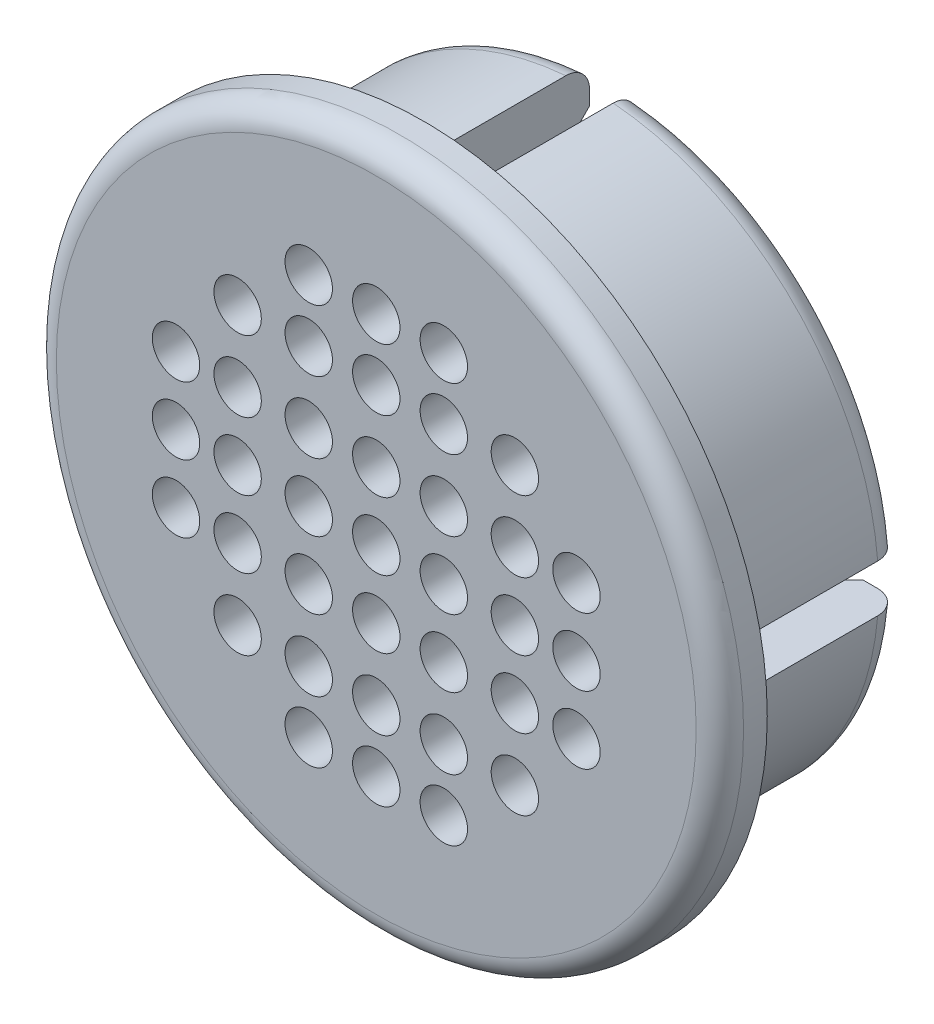
SolidWorks part; units mm, degrees
ref_plane "Front Plane" through (0, 0, 0) normal (0, 0, 1) x (1, 0, 0)
ref_plane "Top Plane" through (0, 0, 0) normal (0, 1, 0) x (1, 0, 0)
ref_plane "Right Plane" through (0, 0, 0) normal (1, 0, 0) x (0, 0, -1)
sketch "Sketch2" plane through (0, 0, 0) normal (1, 0, 0) x (0, 0, -1)
  line L0 (0, 0) -> (10, 0) construction
  line L1 (0, 0) -> (0, 7.25)
  line L2 (0, 7.25) -> (1, 7.25)
  line L3 (1, 7.25) -> (1, 6.1)
  line L4 (1, 6.1) -> (5, 6.1)
  line L5 (5, 6.1) -> (5, 5.1)
  line L6 (5, 5.1) -> (1, 5.1)
  line L7 (1, 5.1) -> (1, 0)
  line L8 (1, 0) -> (0, 0)
  dimension "D1" = 10
  dimension "D2" = 7.25
  dimension "D3" = 5.1
  dimension "D4" = 6.1
  dimension "D5" = 5
  dimension "D6" = 1
  dimension "D7" = 1
revolve "Revolve1" add sketch "Sketch2" angle 360 about L0
sketch "Sketch3" plane through (0, 0, 0) normal (0, 0, 1) x (1, 0, 0)
  line L0 (-2.925, 2.925) -> (2.925, 2.925)
  line L1 (-1.425, 1.425) -> (1.425, 1.425)
  line L2 (-1.425, 1.425) -> (-1.425, -1.425)
  line L3 (-1.425, -1.425) -> (1.425, -1.425)
  line L4 (1.425, 1.425) -> (1.425, -1.425)
  line L5 (-1.425, 1.425) -> (1.425, -1.425) construction
  line L6 (-1.425, -1.425) -> (1.425, 1.425) construction
  line L7 (2.925, 2.925) -> (2.925, -2.925)
  line L8 (-2.925, -2.925) -> (2.925, -2.925)
  line L9 (-2.925, 2.925) -> (-2.925, -2.925)
  line L10 (-2.925, 2.925) -> (0, 2.925) construction
  line L11 (0, 2.925) -> (2.925, 2.925) construction
  line L12 (-4.225, 4.225) -> (4.225, 4.225)
  line L13 (4.225, 4.225) -> (4.225, -4.225)
  line L14 (-4.225, -4.225) -> (4.225, -4.225)
  line L15 (-4.225, 4.225) -> (-4.225, -4.225)
  circle A0 centre (-1.425, 1.425) radius 0.5
  circle A1 centre (1.425, 1.425) radius 0.5
  circle A2 centre (0, 1.425) radius 0.5
  circle A3 centre (1.425, 0) radius 0.5
  circle A4 centre (1.425, -1.425) radius 0.5
  circle A5 centre (0, -1.425) radius 0.5
  circle A6 centre (-1.425, -1.425) radius 0.5
  circle A7 centre (-1.425, 0) radius 0.5
  circle A9 centre (-2.925, 2.925) radius 0.5
  circle A10 centre (0, 2.925) radius 0.5
  circle A11 centre (2.925, 2.925) radius 0.5
  circle A12 centre (2.925, 0) radius 0.5
  circle A13 centre (2.925, -2.925) radius 0.5
  circle A14 centre (0, -2.925) radius 0.5
  circle A15 centre (-2.925, -2.925) radius 0.5
  circle A16 centre (-2.925, 0) radius 0.5
  circle A17 centre (0, 0) radius 5.1
  circle A18 centre (-1.425, 2.925) radius 0.5
  circle A19 centre (1.425, 2.925) radius 0.5
  circle A20 centre (2.925, 1.425) radius 0.5
  circle A21 centre (2.925, -1.425) radius 0.5
  circle A22 centre (1.425, -2.925) radius 0.5
  circle A23 centre (-1.425, -2.925) radius 0.5
  circle A24 centre (-2.925, -1.425) radius 0.5
  circle A25 centre (-2.925, 1.425) radius 0.5
  circle A26 centre (-1.425, 4.225) radius 0.5
  circle A27 centre (0, 4.225) radius 0.5
  circle A28 centre (1.425, 4.225) radius 0.5
  circle A29 centre (4.225, 1.425) radius 0.5
  circle A30 centre (4.225, 0) radius 0.5
  circle A31 centre (4.225, -1.425) radius 0.5
  circle A32 centre (1.425, -4.225) radius 0.5
  circle A33 centre (0, -4.225) radius 0.5
  circle A34 centre (-1.425, -4.225) radius 0.5
  circle A35 centre (-4.225, -1.425) radius 0.5
  circle A36 centre (-4.225, 0) radius 0.5
  circle A37 centre (-4.225, 1.425) radius 0.5
  circle A38 centre (0, 0) radius 0.5
  point P0 (0, 0)
  dimension "D3" = 1
  dimension "D4" = 1
  dimension "D5" = 1
  dimension "D6" = 1
  dimension "D7" = 1
  dimension "D8" = 1
  dimension "D9" = 1
  dimension "D10" = 1
  dimension "D12" = 10.2
  dimension "D14" = 1
  dimension "D1" = 2.85
  dimension "D2" = 2.85
  dimension "D11" = 1.5
  dimension "D13" = 1.3
extrude "Cut-Extrude1" cut sketch "Sketch3" against normal blind 10 contours A26 | A27 | A28 | A19 | A11 | A10 | A18 | A9 | A37 | A25 | A0 | A2 | A1 | A20 | A29 | A30 | A12 | A3 | A7 | A16 | A36 | A35 | A24 | A6 | A5 | A4 | A21 | A31 | A13 | A22 | A14 | A23 | A15 | A34 | A33 | A32 | A38
fillet "Fillet1" radius 0.5 2 edges at (6.1, 0, -5) (7.25, 0, 0)
chamfer "Chamfer1" distance 0.2 angle 45 1 edges at (5.1, 0, -5)
sketch "Sketch4" plane through (0, 0, -5) normal (0, 0, -1) x (-1, 0, 0)
  line L1 (0.5, -6.25) -> (-0.5, -6.25)
  line L2 (0.5, -6.25) -> (0.5, 6.25)
  line L3 (0.5, 6.25) -> (-0.5, 6.25)
  line L4 (-0.5, -6.25) -> (-0.5, 6.25)
  line L5 (0.5, -6.25) -> (-0.5, 6.25) construction
  line L6 (0.5, 6.25) -> (-0.5, -6.25) construction
  line L7 (-6.25, -0.5) -> (6.25, -0.5)
  line L8 (-6.25, -0.5) -> (-6.25, 0.5)
  line L9 (-6.25, 0.5) -> (6.25, 0.5)
  line L10 (6.25, -0.5) -> (6.25, 0.5)
  line L11 (-6.25, -0.5) -> (6.25, 0.5) construction
  line L12 (-6.25, 0.5) -> (6.25, -0.5) construction
  point P0 (0, 0)
  point P6 (0, 0)
  dimension "D1" = 1
  dimension "D2" = 12.5
  dimension "D3" = 1
  dimension "D4" = 12.5
extrude "Cut-Extrude2" cut sketch "Sketch4" against normal blind 4 contours L3 L4 L1 L2 | L8 L9 L10 L7
